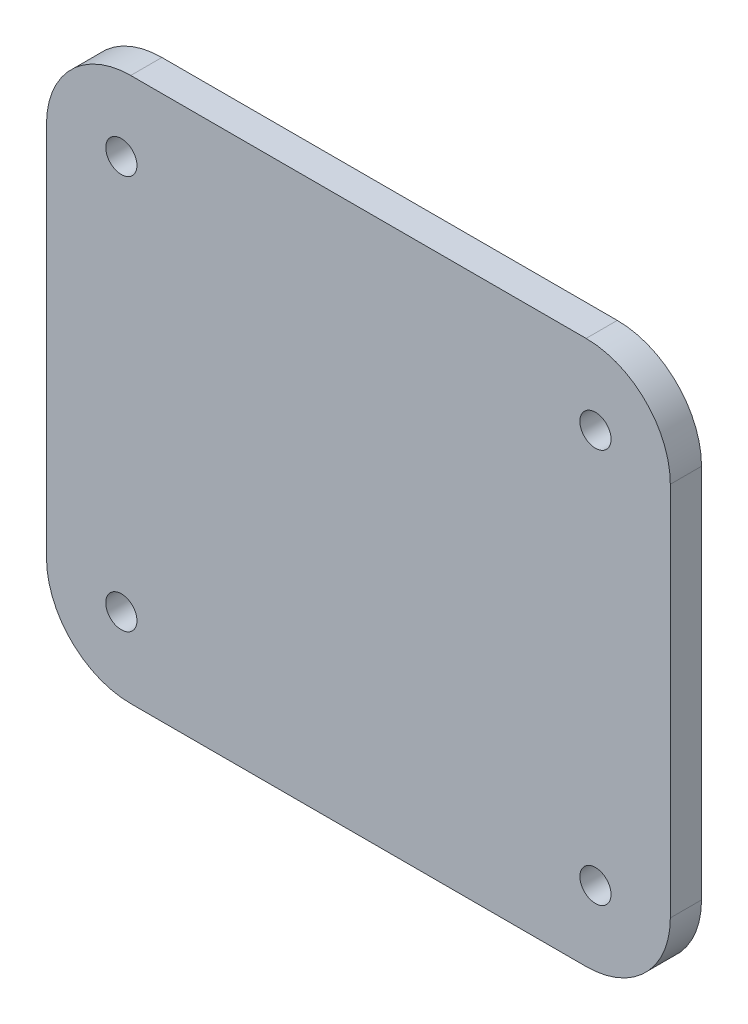
SolidWorks part; units mm, degrees
ref_plane "Ön Düzlem" through (0, 0, 0) normal (0, 0, 1) x (1, 0, 0)
ref_plane "Üst Düzlem" through (0, 0, 0) normal (0, 1, 0) x (1, 0, 0)
ref_plane "Sağ Düzlem" through (0, 0, 0) normal (1, 0, 0) x (0, 0, -1)
sketch "Çizim1" plane through (0, 0, 0) normal (0, 0, 1) x (1, 0, 0)
  line L0 (21, 43.6) -> (50, 43.6)
  line L1 (-50, -43.6) -> (50, -43.6)
  line L2 (-50, -43.6) -> (-50, 43.6)
  line L3 (-50, 43.6) -> (-21, 43.6)
  line L4 (50, -43.6) -> (50, 43.6)
  line L5 (0, 47) -> (0, -43.6) construction
  line L6 (-50, 0) -> (50, 0) construction
  line L12 (-21, 43.6) -> (21, 43.6)
  point P0 (0, 0)
  dimension "D1" = 87.2
  dimension "D2" = 100
extrude "Yükseklik-Ekstrüzyon1" add sketch "Çizim1" along normal blind 5
sketch "Çizim2" plane through (0, 0, 5) normal (0, 0, 1) x (1, 0, 0)
  line L0 (50, -43.6) -> (50, 43.6) construction
  line L1 (-50, -43.6) -> (50, -43.6) construction
  line L2 (50, 43.6) -> (-50, 43.6) construction
  line L3 (50, 43.6) -> (-50, 43.6) construction
  line L4 (-50, 43.6) -> (-50, -43.6) construction
  circle A0 centre (38, -31.6) radius 2.5
  circle A1 centre (38, 31.6) radius 2.5
  circle A7 centre (-38, 31.6) radius 2.5
  circle A8 centre (-38, -31.6) radius 2.5
  dimension "D1" = 5
  dimension "D2" = 12
  dimension "D3" = 12
  dimension "D4" = 5
  dimension "D6" = 12
  dimension "D19" = 5
  dimension "D20" = 5
  dimension "D5" = 12
  dimension "D21" = 12
  dimension "D22" = 12
  dimension "D23" = 12
  dimension "D24" = 12
extrude "Kes-Ekstrüzyon1" cut sketch "Çizim2" against normal blind 10
fillet "Radyus1" radius 13.5 4 edges at (-50, -43.6, 2.5) (50, -43.6, 2.5) (50, 43.6, 2.5) (-50, 43.6, 2.5)
